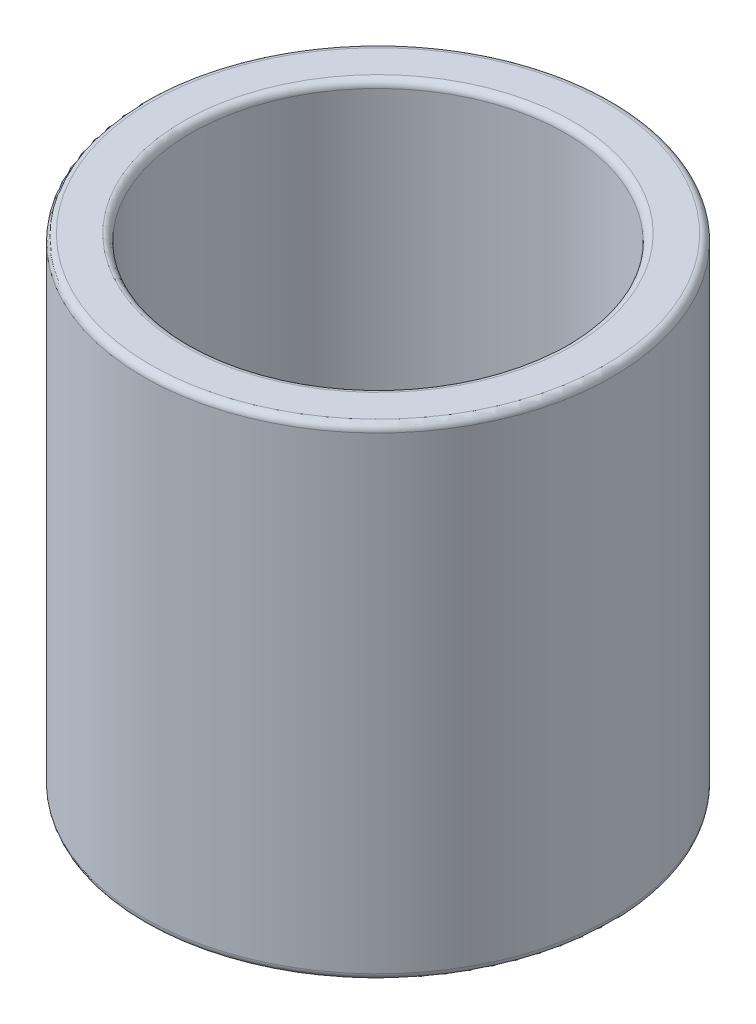
SolidWorks part; units mm, degrees
ref_plane "Front Plane" through (0, 0, 0) normal (0, 0, 1) x (1, 0, 0)
ref_plane "Top Plane" through (0, 0, 0) normal (0, 1, 0) x (1, 0, 0)
ref_plane "Right Plane" through (0, 0, 0) normal (1, 0, 0) x (0, 0, -1)
sketch "Sketch1" plane through (0, 0, 0) normal (0, 1, 0) x (1, 0, 0)
  circle A0 centre (0, 0) radius 4
  circle A1 centre (0, 0) radius 5
  dimension "D1" = 8
  dimension "D2" = 10
extrude "Boss-Extrude1" add sketch "Sketch1" along normal blind 10.287
fillet "Fillet1" radius 0.15 4 edges at (0, 10.287, 4) (0, 0, 4) (0, 0, 5) (0, 10.287, 5)
